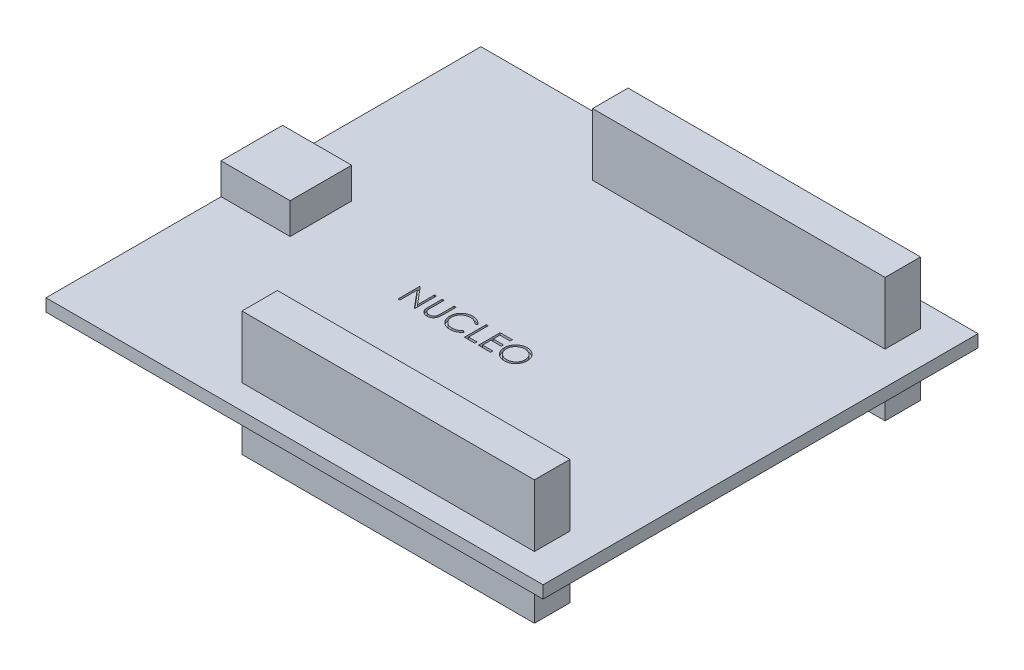
SolidWorks part; units mm, degrees
ref_plane "Front Plane" through (0, 0, 0) normal (0, 0, 1) x (1, 0, 0)
ref_plane "Top Plane" through (0, 0, 0) normal (0, 1, 0) x (1, 0, 0)
ref_plane "Right Plane" through (0, 0, 0) normal (1, 0, 0) x (0, 0, -1)
sketch "Sketch1" plane through (0, 0, 0) normal (0, 1, 0) x (1, 0, 0)
  line L1 (0, 0) -> (80, 0)
  line L2 (0, 0) -> (0, 70)
  line L3 (0, 70) -> (80, 70)
  line L4 (80, 0) -> (80, 70)
  dimension "D1" = 70
  dimension "D2" = 80
extrude "Boss-Extrude1" add sketch "Sketch1" along normal blind 2
sketch "Sketch2" plane through (0, 2, 0) normal (0, 1, 0) x (1, 0, 0)
  line L0 (49.8962, 70) -> (49.8962, 66.0705) construction
  line L1 (27.6075, 9.6354) -> (74.6813, 9.6354)
  line L2 (27.6075, 9.6354) -> (27.6075, 3.9295)
  line L3 (27.6075, 3.9295) -> (74.6813, 3.9295)
  line L4 (74.6813, 9.6354) -> (74.6813, 3.9295)
  line L5 (27.6075, 66.0705) -> (74.6813, 66.0705)
  line L6 (27.6075, 66.0705) -> (27.6075, 60.3646)
  line L7 (27.6075, 60.3646) -> (74.6813, 60.3646)
  line L8 (74.6813, 66.0705) -> (74.6813, 60.3646)
  line L9 (80, 70) -> (0, 70) construction
  line L10 (51.1444, 3.9295) -> (51.1444, 0) construction
  line L11 (0, 0) -> (80, 0) construction
extrude "Boss-Extrude2" add sketch "Sketch2" along normal mid plane 20
sketch "Sketch3" plane through (0, 2, 0) normal (0, 1, 0) x (1, 0, 0)
  line L0 (0, 70) -> (0, 0) construction
  line L2 (11.1138, 28.1796) -> (0, 28.1796)
  line L3 (11.1138, 28.1796) -> (11.1138, 38.0758)
  line L4 (11.1138, 38.0758) -> (0, 38.0758)
  line L5 (0, 28.1796) -> (0, 38.0758)
extrude "Boss-Extrude3" add sketch "Sketch3" along normal blind 5
sketch "Sketch4" plane through (0, 2, 0) normal (0, 1, 0) x (1, 0, 0)
  line L0 (28.0385, 28.1796) -> (67.7416, 28.1796) construction
  line L1 (28.0385, 28.1796) -> (28.0385, 40.3166) construction
  text T0 "NUCLEO"
extrude "Cut-Extrude1" cut sketch "Sketch4" against normal blind 0.5
